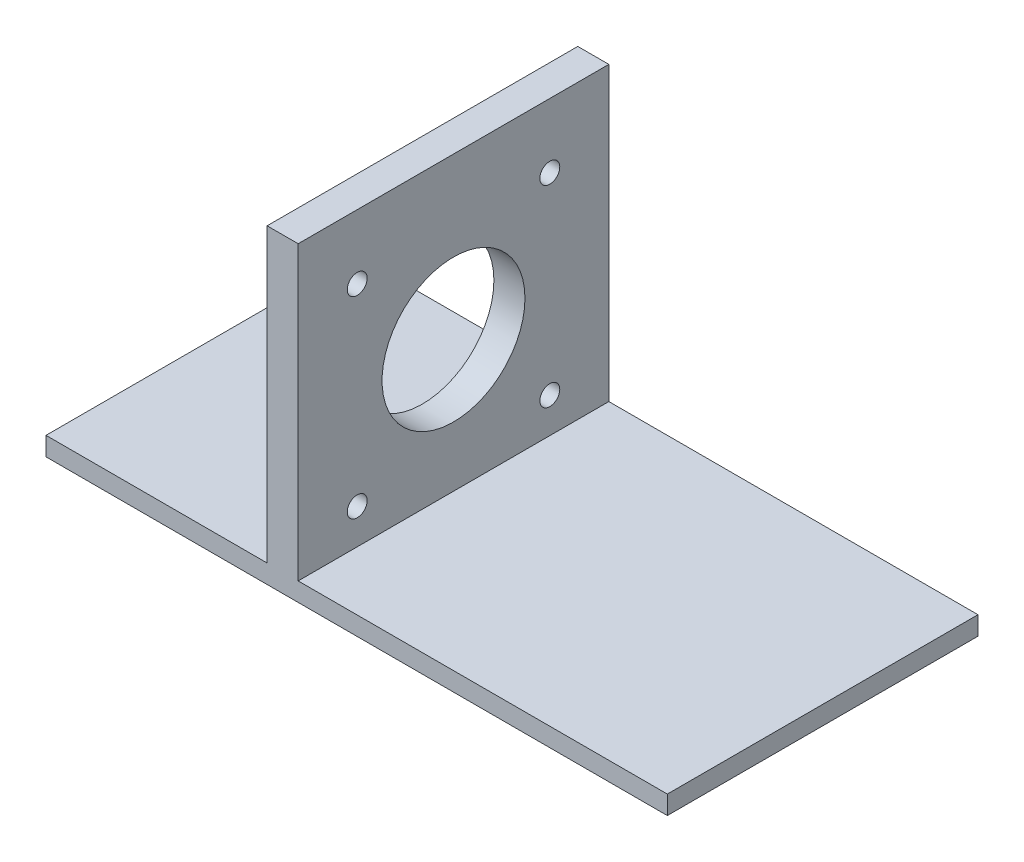
SolidWorks part; units mm, degrees
ref_plane "Front Plane" through (0, 0, 0) normal (0, 0, 1) x (1, 0, 0)
ref_plane "Top Plane" through (0, 0, 0) normal (0, 1, 0) x (1, 0, 0)
ref_plane "Right Plane" through (0, 0, 0) normal (1, 0, 0) x (0, 0, -1)
sketch "Sketch1" plane through (0, 0, 0) normal (0, 1, 0) x (1, 0, 0)
  line L1 (-50, -25) -> (50, -25)
  line L2 (-50, -25) -> (-50, 25)
  line L3 (-50, 25) -> (50, 25)
  line L4 (50, -25) -> (50, 25)
  line L5 (-50, -25) -> (50, 25) construction
  line L6 (-50, 25) -> (50, -25) construction
  point P0 (0, 0)
extrude "Boss-Extrude1" add sketch "Sketch1" along normal blind 3
sketch "Sketch2" plane through (0, 3, 0) normal (0, 1, 0) x (1, 0, 0)
  line L0 (-9.413, 25) -> (-14.413, 25)
  line L1 (50, 25) -> (-50, 25) construction
  line L2 (-14.413, 25) -> (-14.413, -25)
  line L3 (-50, -25) -> (50, -25) construction
  line L4 (-14.413, -25) -> (-9.413, -25)
  line L5 (-9.413, -25) -> (-9.413, 25)
extrude "Boss-Extrude3" add sketch "Sketch2" along normal blind 47
sketch "Sketch8" plane through (-9.413, 0, 0) normal (1, 0, 0) x (0, 0, -1)
  circle A0 centre (0, 24.15) radius 11.5
extrude "Cut-Extrude3" cut sketch "Sketch8" against normal through all
sketch "Sketch9" plane through (-9.413, 0, 0) normal (1, 0, 0) x (0, 0, -1)
  circle A0 centre (-15.5, 8.65) radius 1.6
  circle A1 centre (-15.5, 39.65) radius 1.6
  circle A2 centre (15.5, 39.65) radius 1.6
  circle A3 centre (15.5, 8.65) radius 1.6
extrude "Cut-Extrude4" cut sketch "Sketch9" against normal through all
